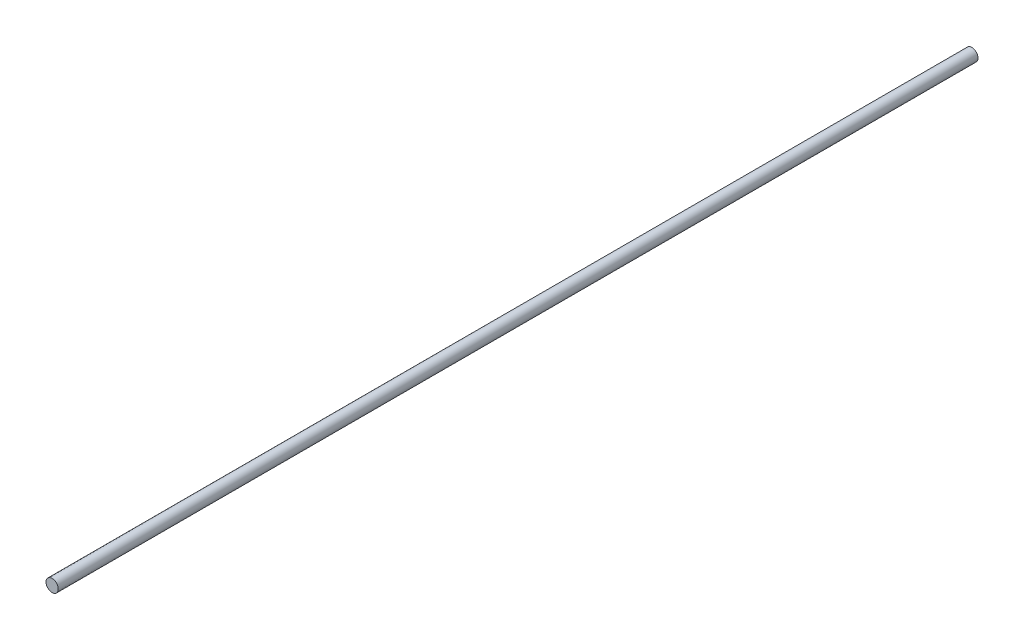
SolidWorks part; units mm, degrees
material "Hexcel AS4C (3000 Filaments)"
ref_plane "Front Plane" through (0, 0, 0) normal (0, 0, 1) x (1, 0, 0)
ref_plane "Top Plane" through (0, 0, 0) normal (0, 1, 0) x (1, 0, 0)
ref_plane "Right Plane" through (0, 0, 0) normal (1, 0, 0) x (0, 0, -1)
sketch "Sketch1" plane through (0, 0, 0) normal (0, 0, 1) x (1, 0, 0)
  circle A0 centre (0, 0) radius 1
  dimension "D1" = 2
extrude "Boss-Extrude1" add sketch "Sketch1" along normal blind 150
